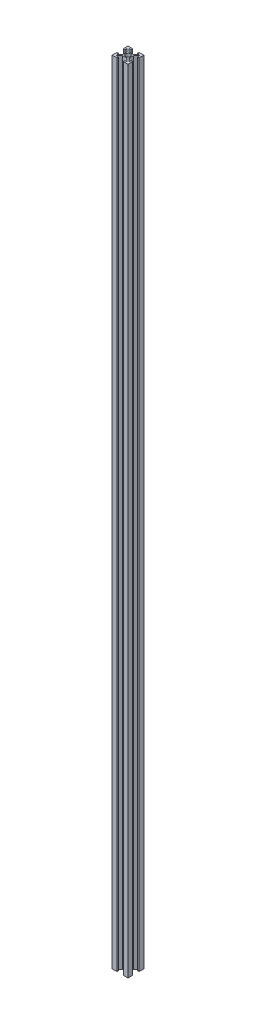
SolidWorks part; units mm, degrees
material "1060 Alloy"
ref_plane "Front Plane" through (0, 0, 0) normal (0, 0, 1) x (1, 0, 0)
ref_plane "Top Plane" through (0, 0, 0) normal (0, 1, 0) x (1, 0, 0)
ref_plane "Right Plane" through (0, 0, 0) normal (1, 0, 0) x (0, 0, -1)
sketch "2020 sketch" plane through (0, 0, 0) normal (0, 1, 0) x (1, 0, 0)
  line L0 (-4, 10) -> (-4, 8)
  line L1 (-10, 10) -> (-4, 10)
  line L2 (-10, 10) -> (-10, 4)
  line L3 (-10, -10) -> (-4, -10)
  line L4 (10, 10) -> (10, 4)
  line L5 (-10, 10) -> (10, -10) construction
  line L6 (-10, -10) -> (10, 10) construction
  line L7 (-4, 8) -> (-7, 8)
  line L8 (-7, 8) -> (-3, 4)
  line L9 (-3, 4) -> (3, 4)
  line L10 (3, 4) -> (7, 8)
  line L11 (7, 8) -> (4, 8)
  line L12 (4, 8) -> (4, 10)
  line L13 (4, 3) -> (4, -3)
  line L14 (8, 7) -> (4, 3)
  line L15 (8, 4) -> (8, 7)
  line L16 (10, 4) -> (8, 4)
  line L17 (8, -4) -> (10, -4)
  line L18 (8, -7) -> (8, -4)
  line L19 (4, -3) -> (8, -7)
  line L20 (3, -4) -> (-3, -4)
  line L21 (7, -8) -> (3, -4)
  line L22 (4, -8) -> (7, -8)
  line L23 (4, -10) -> (4, -8)
  line L24 (-4, -8) -> (-4, -10)
  line L25 (-7, -8) -> (-4, -8)
  line L26 (-3, -4) -> (-7, -8)
  line L27 (-4, -3) -> (-4, 3)
  line L28 (-8, -7) -> (-4, -3)
  line L29 (-8, -4) -> (-8, -7)
  line L30 (-10, -4) -> (-8, -4)
  line L31 (-8, 4) -> (-10, 4)
  line L32 (-8, 7) -> (-8, 4)
  line L33 (-4, 3) -> (-8, 7)
  line L34 (-10, -4) -> (-10, -10)
  line L35 (10, -4) -> (10, -10)
  line L36 (4, 10) -> (10, 10)
  line L37 (4, -10) -> (10, -10)
  circle A0 centre (0, 0) radius 3
  point P0 (0, 0)
  point P14 (4, 9)
  point P42 (0, 0)
  dimension "D9" = 6
  dimension "D1" = 20
  dimension "D2" = 20
  dimension "D3" = 8
  dimension "D4" = 6
  dimension "D5" = 6
  dimension "D6" = 2
  dimension "D7" = 4
  dimension "D8" = 4
extrude "Boss-Extrude1" add sketch "2020 sketch" along normal blind 1000 contours A0 | L28 L27 L33 L32 L31 L2 L1 L0 L7 L8 L9 L10 L11 L12 L36 L4 L16 L15 L14 L13 L19 L18 L17 L35 L37 L23 L22 L21 L20 L26 L25 L24 L3 L34 L30 L29
